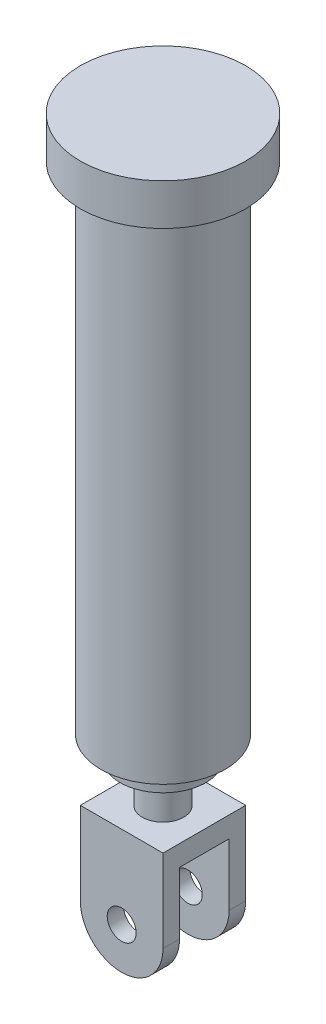
SolidWorks part; units mm, degrees
material "6061-T6 (SS)"
ref_plane "Front Plane" through (0, 0, 0) normal (0, 0, 1) x (1, 0, 0)
ref_plane "Top Plane" through (0, 0, 0) normal (0, 1, 0) x (1, 0, 0)
ref_plane "Right Plane" through (0, 0, 0) normal (1, 0, 0) x (0, 0, -1)
sketch "Sketch3" plane through (0, 0, 0) normal (0, 1, 0) x (1, 0, 0)
  circle A0 centre (0, 0) radius 20
  dimension "D1" = 40
extrude "Boss-Extrude1" add sketch "Sketch3" against normal blind 10 contours A0
sketch "Sketch4" plane through (0, -10, 0) normal (0, -1, 0) x (1, 0, 0)
  circle A0 centre (0, 0) radius 15
  dimension "D1" = 30
extrude "Boss-Extrude2" add sketch "Sketch4" along normal blind 120 contours A0
sketch "Sketch5" plane through (0, -130, 0) normal (0, -1, 0) x (1, 0, 0)
  circle A0 centre (0, 0) radius 10.4359
extrude "Boss-Extrude3" add sketch "Sketch5" along normal blind 5 contours A0
sketch "Sketch6" plane through (0, -135, 0) normal (0, -1, 0) x (-1, 0, 0)
  circle A0 centre (0, 0) radius 5
  dimension "D1" = 10
extrude "Boss-Extrude4" add sketch "Sketch6" along normal blind 10 contours A0
sketch "Sketch7" plane through (0, -145, 0) normal (0, -1, 0) x (1, 0, 0)
  line L1 (-10, -10) -> (10, -10)
  line L2 (-10, -10) -> (-10, 10)
  line L3 (-10, 10) -> (10, 10)
  line L4 (10, -10) -> (10, 10)
  line L5 (-10, -10) -> (10, 10) construction
  line L6 (-10, 10) -> (10, -10) construction
  point P0 (0, 0)
  dimension "D1" = 20
  dimension "D2" = 20
extrude "Boss-Extrude5" add sketch "Sketch7" along normal blind 5 contours L2 L1 L4 L3
sketch "Sketch8" plane through (0, 0, -10) normal (0, 0, -1) x (-1, 0, 0)
  line L0 (-10, -150) -> (-10, -165)
  line L1 (10, -165) -> (10, -150)
  line L2 (-10, -150) -> (10, -150)
  arc A0 (-10, -165) -> (10, -165) centre (0, -165) ccw
  circle A1 centre (0, -165) radius 3.5
  dimension "D2" = 7
  dimension "D1" = 15
extrude "Boss-Extrude6" add sketch "Sketch8" against normal blind 20 contours A1 | L2 L1 A0 L0
cosmetic thread "Cosmetic Thread1" parameters "D1"=19.9999, "D2"=8
sketch "Sketch9" plane through (-10, 0, 0) normal (-1, 0, 0) x (0, 0, 1)
  line L0 (-10, -175) -> (10, -175) construction
  line L1 (6, -175) -> (-6, -175)
  line L2 (6, -175) -> (6, -150)
  line L3 (6, -150) -> (-6, -150)
  line L4 (-6, -175) -> (-6, -150)
  line L5 (10, -175) -> (10, -165) construction
  dimension "D1" = 12
  dimension "D2" = 25
  dimension "D3" = 4
extrude "Cut-Extrude1" cut sketch "Sketch9" against normal mid plane 54
